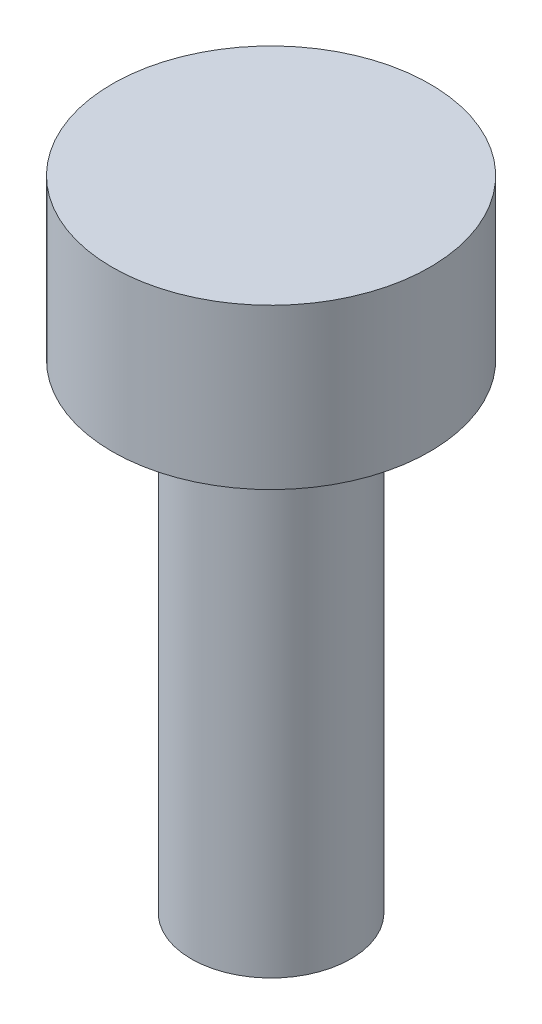
SolidWorks part; units mm, degrees
other "Retainer Screw ISO4762 M2x6"
other "Retainer Screw ISO4762 M2x6 Left"
ref_plane "Front Plane" through (0, 0, 0) normal (0, 0, 1) x (1, 0, 0)
ref_plane "Top Plane" through (0, 0, 0) normal (0, 1, 0) x (1, 0, 0)
ref_plane "Right Plane" through (0, 0, 0) normal (1, 0, 0) x (0, 0, -1)
sketch3d "M2x6 full-thread envelope sketch datum points"
  point P0 (-26.2917, -73, -8.5)
  point P1 (-16.2917, -73, -8.5)
  point P2 (-26.2917, -73, -18.5)
ref_plane "M2x6 full-thread envelope sketch plane" through (0, -73, 0) normal (0, 1, 0) x (1, 0, 0)
sketch "M2x6 full-thread envelope sketch" plane through (0, -73, 0) normal (0, 1, 0) x (1, 0, 0)
  circle A0 centre (-26.2917, 8.5) radius 1
extrude "M2x6 full-thread envelope" add sketch "M2x6 full-thread envelope sketch" along normal blind 6 separate body
sketch3d "Purchased DIN912 maximum head sketch datum points"
  point P0 (-26.2917, -75, -8.5)
  point P1 (-16.2917, -75, -8.5)
  point P2 (-26.2917, -75, -18.5)
ref_plane "Purchased DIN912 maximum head sketch plane" through (0, -75, 0) normal (0, 1, 0) x (1, 0, 0)
sketch "Purchased DIN912 maximum head sketch" plane through (0, -75, 0) normal (0, 1, 0) x (1, 0, 0)
  circle A0 centre (-26.2917, 8.5) radius 1.99
extrude "Purchased DIN912 maximum head" add sketch "Purchased DIN912 maximum head sketch" along normal blind 2
sketch3d "Mirror1 profile datum points"
  point P0 (0, 0, 0)
  point P1 (10, 0, 0)
  point P2 (0, 0, 10)
ref_plane "Mirror1 profile plane" through (0, 0, 0) normal (0, -1, 0) x (-1, 0, 0)
mirror "Mirror1" about plane through (0, 0, 0) normal (0, -1, 0) of bodies 102
delete or keep bodies "Remove1" type delete bodies bodies 102
